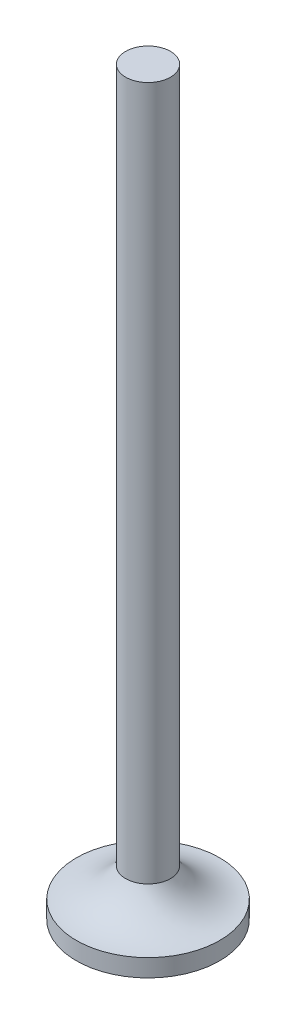
SolidWorks part; units mm, degrees
material "AISI 316 Annealed Stainless Steel Bar (SS)"
ref_plane "Front Plane" through (0, 0, 0) normal (0, 0, 1) x (1, 0, 0)
ref_plane "Top Plane" through (0, 0, 0) normal (0, 1, 0) x (1, 0, 0)
ref_plane "Right Plane" through (0, 0, 0) normal (1, 0, 0) x (0, 0, -1)
sketch "Sketch1" plane through (0, 0, 0) normal (0, 0, 1) x (1, 0, 0)
  line L0 (0, -31.8317) -> (0, 59.5919) construction
  line L1 (0, 0) -> (10.16, 0)
  line L2 (10.16, 0) -> (10.16, 2.5)
  line L4 (3.175, 6.6) -> (3.175, 105)
  line L5 (3.175, 105) -> (0, 105)
  line L6 (0, 105) -> (0, 0)
  arc A0 (10.16, 2.5) -> (3.175, 6.6) centre (10.16, 10.5) cw
  dimension "D5" = 8
  dimension "D1" = 10.16
  dimension "D2" = 3.175
  dimension "D3" = 2.5
  dimension "D4" = 105
revolve "Revolve1" add sketch "Sketch1" angle 360 about L0
cosmetic thread "Cosmetic Thread1" parameters "D1"=12, "D2"=5.268
